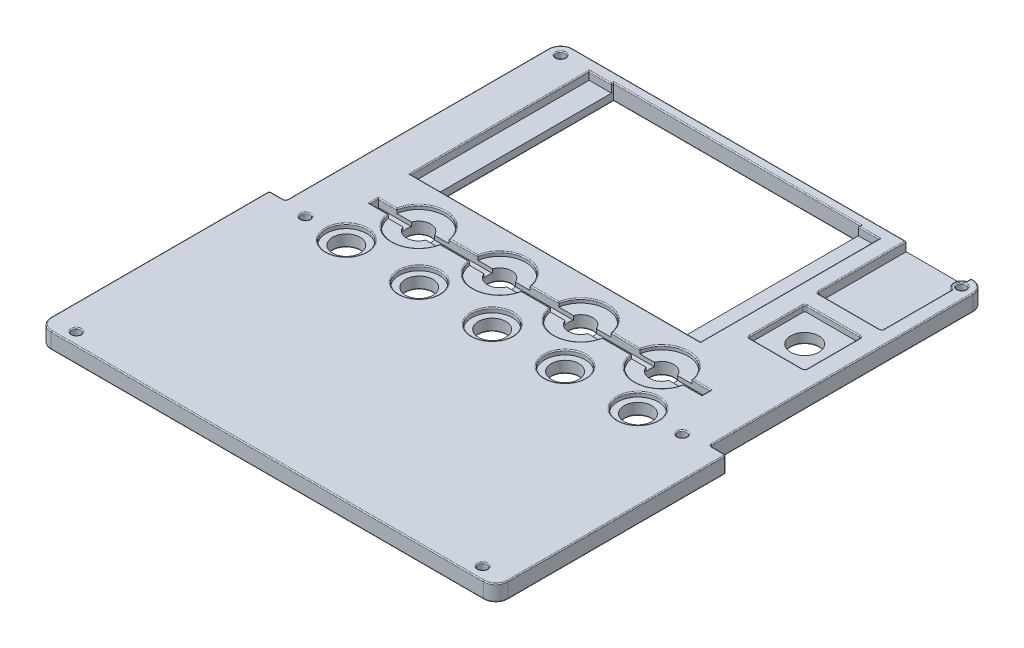
SolidWorks part; units mm, degrees
ref_plane "Front Plane" through (0, 0, 0) normal (0, 0, 1) x (1, 0, 0)
ref_plane "Top Plane" through (0, 0, 0) normal (0, 1, 0) x (1, 0, 0)
ref_plane "Right Plane" through (0, 0, 0) normal (1, 0, 0) x (0, 0, -1)
sketch "Sketch1" plane through (0, 0, 0) normal (0, 1, 0) x (1, 0, 0)
  line L0 (112.8, 56.9) -> (108.8, 56.9)
  line L1 (0, 0) -> (112.8, 0)
  line L2 (0, 0) -> (0, 56.9)
  line L3 (0, 56.9) -> (112.8, 56.9) construction
  line L4 (112.8, 0) -> (112.8, 56.9)
  line L5 (4, 56.9) -> (0, 56.9)
  line L6 (4, 56.9) -> (4, 124.8)
  line L7 (4, 124.8) -> (108.8, 124.8)
  line L8 (108.8, 56.9) -> (108.8, 124.8)
  line L9 (0, 56.9) -> (112.8, 56.9) construction
  dimension "D1" = 104.8
  dimension "D2" = 112.8
  dimension "D3" = 67.9
  dimension "D4" = 56.9
extrude "Main" add sketch "Sketch1" along normal blind 4
sketch "Outline Display" plane through (0, 0, 0) normal (0, -1, 0) x (1, 0, 0)
  line L0 (4, -124.8) -> (4, -81.05) construction
  line L1 (4, -124.8) -> (4, -56.9) construction
  line L2 (4, -81.05) -> (17, -81.05) construction
  line L3 (17, -81.05) -> (17, -78.32) construction
  line L4 (14.23, -78.32) -> (85.03, -78.32) construction
  line L5 (14.23, -78.32) -> (14.23, -121.62) construction
  line L6 (14.23, -121.62) -> (85.03, -121.62) construction
  line L7 (85.03, -78.32) -> (85.03, -121.62) construction
  line L8 (17, -81.05) -> (14.23, -81.05) construction
  point P7 (17, -81.05)
  dimension "D1" = 43.75
  dimension "D2" = 13
  dimension "D3" = 2.73
  dimension "D4" = 2.77
  dimension "D5" = 43.3
  dimension "D6" = 70.8
sketch "Display PCB Notch" plane through (0, 4, 0) normal (0, -1, 0) x (1, 0, 0)
  line L0 (14.23, -78.32) -> (14.23, -77.92) construction
  line L1 (13.83, -77.92) -> (85.43, -77.92)
  line L2 (13.83, -77.92) -> (13.83, -122.02)
  line L3 (13.83, -122.02) -> (85.43, -122.02)
  line L4 (85.43, -77.92) -> (85.43, -122.02)
  line L5 (14.23, -78.32) -> (13.83, -78.32) construction
  line L6 (85.03, -121.62) -> (85.03, -122.02) construction
  line L7 (85.03, -121.62) -> (85.43, -121.62) construction
  dimension "D2" = 0.4
extrude "PCB Notch" cut sketch "Display PCB Notch" along normal blind 2
sketch "Sketch4" plane through (0, 0, 0) normal (0, -1, 0) x (-1, 0, 0)
  line L0 (-14.23, 78.32) -> (-85.03, 78.32) construction
  line L1 (-19.33, 78.87) -> (-80.29, 78.87)
  line L2 (-19.33, 78.87) -> (-19.33, 122.57)
  line L3 (-19.33, 122.57) -> (-80.29, 122.57)
  line L4 (-80.29, 78.87) -> (-80.29, 122.57)
  dimension "D1" = 5.1
  dimension "D2" = 0.55
  dimension "D3" = 60.96
  dimension "D4" = 43.7
extrude "Display Cut" cut sketch "Sketch4" against normal up to next
sketch "Sketch5" plane through (0, 0, 0) normal (0, -1, 0) x (1, 0, 0)
  line L0 (108.8, -56.9) -> (108.8, -124.8) construction
  line L1 (89.12, -102.2) -> (97.32, -102.2) construction
  line L2 (97.32, -102.2) -> (97.32, -91.75) construction
  circle A0 centre (97.32, -91.75) radius 3.5
  point P0 (89.12, -102.2)
  point P1 (108.8, -124.8)
  point P9 (97.32, -91.75)
  dimension "D5" = 7
  dimension "D1" = 22.6
  dimension "D2" = 19.68
  dimension "D3" = 10.45
  dimension "D4" = 8.2
extrude "Rotary Hole" cut sketch "Sketch5" against normal up to next
sketch "Sketch6" plane through (0, 0, 0) normal (0, -1, 0) x (1, 0, 0)
  line L0 (6.9, -124.8) -> (6.9, -121.9) construction
  line L1 (108.8, -124.8) -> (4, -124.8) construction
  line L2 (6.9, -121.9) -> (4, -121.9) construction
  line L3 (4, -124.8) -> (4, -56.9) construction
  line L4 (56.4, 0) -> (56.4, -124.8) construction
  line L5 (0, 0) -> (112.8, 0) construction
  line L6 (0, -55.9) -> (9.9, -55.9) construction
  line L7 (0, -56.9) -> (0, 0) construction
  line L8 (4, -56.9) -> (0, -56.9) construction
  line L9 (0, -3) -> (6.25, -3) construction
  circle A0 centre (6.9, -121.9) radius 1.1
  circle A1 centre (9.9, -55.9) radius 1.1
  circle A2 centre (6.25, -3) radius 1.1
  circle A3 centre (105.9, -121.9) radius 1.1
  circle A4 centre (102.9, -55.9) radius 1.1
  circle A5 centre (106.55, -3) radius 1.1
  dimension "D1" = 2.2
  dimension "D7" = 6.25
  dimension "D2" = 2.9
  dimension "D3" = 2.9
  dimension "D4" = 9.9
  dimension "D5" = 1
  dimension "D6" = 3
extrude "Mounts" cut sketch "Sketch6" against normal up to next contours A0 | A1 | A2 | A5 | A4 | A3
fillet "Fillet1" radius 3 4 edges at (112.8, 2, 0) (108.8, 2, -124.8) (4, 2, -124.8) (0, 2, 0)
sketch "Sketch7" plane through (0, 0, 0) normal (0, -1, 0) x (1, 0, 0)
  line L0 (17, -81.05) -> (17, -75.8) construction
  line L1 (17, -59.7) -> (4, -59.7) construction
  line L2 (17, -75.8) -> (95.8, -75.8)
  line L3 (17, -75.8) -> (17, -59.7)
  line L4 (17, -59.7) -> (95.8, -59.7)
  line L5 (95.8, -75.8) -> (95.8, -59.7)
  line L6 (4, -121.8) -> (4, -56.9) construction
  line L7 (95.8, -59.7) -> (108.8, -59.7) construction
  line L8 (108.8, -56.9) -> (108.8, -121.8) construction
  line L9 (17, -67.75) -> (95.8, -67.75) construction
  circle A0 centre (26, -67.75) radius 3
  circle A1 centre (46, -67.75) radius 3
  circle A2 centre (66, -67.75) radius 3
  circle A3 centre (86, -67.75) radius 3
  dimension "D3" = 6
  dimension "D1" = 5.25
  dimension "D2" = 16.1
  dimension "D4" = 9
  dimension "D5" = 20
  dimension "D6" = 20
  dimension "D7" = 20
extrude "Toggle Mounts" cut sketch "Sketch7" against normal up to next contours A0 | A1 | A2 | A3
sketch "Sketch8" plane through (0, 4, 0) normal (0, -1, 0) x (1, 0, 0)
  line L0 (89, -67.75) -> (23, -67.75) construction
  line L1 (97, -67.75) -> (89, -67.75) construction
  line L2 (97, -68.8) -> (15, -68.8)
  line L3 (97, -68.8) -> (97, -66.7)
  line L4 (97, -66.7) -> (15, -66.7)
  line L5 (15, -68.8) -> (15, -66.7)
  line L6 (23, -67.75) -> (15, -67.75) construction
  line L7 (23, -67.75) -> (23, -68.8) construction
  line L8 (23, -67.75) -> (23, -66.7) construction
  circle A0 centre (86, -67.75) radius 3 construction
  circle A1 centre (26, -67.75) radius 3 construction
  circle A2 centre (86, -67.75) radius 3 construction
  circle A3 centre (86, -67.75) radius 3 construction
  circle A4 centre (26, -67.75) radius 3 construction
  circle A5 centre (26, -67.75) radius 3 construction
  dimension "D1" = 8
  dimension "D2" = 2.1
extrude "Toggle Direction" cut sketch "Sketch8" along normal blind 2
sketch "Sketch9" plane through (0, 4, 0) normal (0, 1, 0) x (1, 0, 0)
  circle A0 centre (26, 67.75) radius 6.5
  circle A1 centre (46, 67.75) radius 6.5
  circle A2 centre (66, 67.75) radius 6.5
  circle A3 centre (86, 67.75) radius 6.5
  point P0 (26, 67.75)
  point P1 (46, 67.75)
  point P3 (66, 67.75)
  point P5 (86, 67.75)
  dimension "D1" = 13
extrude "Toggle Countersinks" cut sketch "Sketch9" against normal blind 1
sketch "Sketch10" plane through (0, 4, 0) normal (0, 1, 0) x (1, 0, 0)
  line L1 (90.32, 98.75) -> (104.32, 98.75)
  line L2 (90.32, 98.75) -> (90.32, 84.75)
  line L3 (90.32, 84.75) -> (104.32, 84.75)
  line L4 (104.32, 98.75) -> (104.32, 84.75)
  line L5 (90.32, 98.75) -> (104.32, 84.75) construction
  line L6 (90.32, 84.75) -> (104.32, 98.75) construction
  point P0 (97.32, 91.75)
  point P1 (97.32, 91.75)
  dimension "D1" = 14
extrude "Encoder Clearance" cut sketch "Sketch10" against normal blind 1.5
sketch "Sketch11" plane through (0, 4, 0) normal (0, 1, 0) x (1, 0, 0)
  line L0 (105.8, 124.8) -> (7, 124.8) construction
  line L1 (89.32, 102.75) -> (105.32, 102.75)
  line L2 (89.32, 102.75) -> (89.32, 124.8)
  line L3 (89.32, 124.8) -> (105.32, 124.8)
  line L4 (105.32, 102.75) -> (105.32, 120.0907)
  line L5 (89.32, 102.75) -> (105.32, 124.8) construction
  line L6 (89.32, 124.8) -> (105.32, 102.75) construction
  line L7 (105.32, 123.7093) -> (105.32, 124.8)
  line L8 (105.32, 120.0907) -> (105.32, 123.7093) construction
  line L10 (104.32, 84.75) -> (104.32, 98.75)
  line L11 (104.32, 98.75) -> (90.32, 98.75)
  line L12 (90.32, 98.75) -> (90.32, 84.75)
  line L13 (90.32, 84.75) -> (104.32, 84.75)
  line L14 (104.32, 84.75) -> (104.32, 98.75) construction
  line L15 (104.32, 98.75) -> (90.32, 98.75) construction
  line L16 (90.32, 98.75) -> (90.32, 84.75) construction
  line L17 (90.32, 84.75) -> (104.32, 84.75) construction
  arc A0 (105.32, 123.7093) -> (105.32, 120.0907) centre (105.9, 121.9) ccw
  circle A1 centre (105.9, 121.9) radius 1.1 construction
  arc A2 (105.32, 120.0907) -> (105.32, 123.7093) centre (105.9, 121.9) ccw construction
  point P4 (97.32, 113.775)
  dimension "D5" = 3.8
  dimension "D2" = 1
  dimension "D3" = 1
  dimension "D4" = 4
  dimension "D1" = 0
extrude "Encoder Pin Clearance" cut sketch "Sketch11" against normal blind 2.3
fillet "Fillet2" radius 0.5 10 edges at (0, 2, -56.9) (4, 2, -56.9) (112.8, 2, -56.9) (108.8, 2, -56.9) (89.32, 2.85, -102.75) (105.32, 2.85, -102.75) (104.32, 3.25, -84.75) (104.32, 3.25, -98.75) (90.32, 3.25, -98.75) (90.32, 3.25, -84.75)
sketch "Sketch12" plane through (0, 4, 0) normal (0, 1, 0) x (1, 0, 0)
  line L0 (9.9, 55.9) -> (102.9, 55.9) construction
  line L1 (38, 66.7) -> (38, 59.3) construction
  line L3 (56, 66.7) -> (56, 59.3) construction
  line L4 (59.5854, 66.7) -> (52.4146, 66.7) construction
  line L5 (74, 66.7) -> (74, 59.3) construction
  line L7 (38, 59.3) -> (20, 59.3) construction
  line L8 (38, 59.3) -> (56, 59.3) construction
  line L9 (74, 59.3) -> (92, 59.3) construction
  line L10 (56, 59.3) -> (74, 59.3) construction
  circle A2 centre (20, 55.9) radius 3.4
  circle A3 centre (38, 55.9) radius 3.4
  circle A4 centre (56, 55.9) radius 3.4
  circle A5 centre (74, 55.9) radius 3.4
  circle A6 centre (92, 55.9) radius 3.4
  point P3 (9.9, 55.9)
  point P4 (102.9, 55.9)
  dimension "D1" = 6.8
  dimension "D2" = 18
extrude "LED Mounts" cut sketch "Sketch12" against normal up to next
sketch "Sketch13" plane through (0, 4, 0) normal (0, 1, 0) x (1, 0, 0)
  circle A0 centre (20, 55.9) radius 5
  circle A1 centre (38, 55.9) radius 5
  circle A2 centre (56, 55.9) radius 5
  circle A3 centre (74, 55.9) radius 5
  circle A4 centre (92, 55.9) radius 5
  point P0 (20, 55.9)
  point P1 (38, 55.9)
  point P3 (56, 55.9)
  point P5 (74, 55.9)
  point P7 (92, 55.9)
  dimension "D1" = 10
extrude "LED Countersink" cut sketch "Sketch13" against normal blind 1.1
fillet "Fillet4" radius 0.25 77 edges at (4.8787, 4, -123.9213) (105.56, 4, -124.8) (48.16, 4, -124.8) (111.9213, 4, -0.8787) (56.4, 4, 0) (56.4, 0, -124.8) (112.8, 0, -29.7) (111.9213, 0, -0.8787) (56.4, 0, 0) (108.9464, 4, -57.0464) (108.9464, 0, -57.0464) (3.8536, 4, -57.0464) (3.8536, 0, -57.0464) (90.4664, 4, -84.8964) (90.4664, 4, -98.6036) (104.1736, 4, -98.6036) (104.1736, 4, -84.8964) (89.4664, 4, -102.8964) (0.1464, 4, -56.7536) (107.9213, 4, -123.9213) (107.9213, 0, -123.9213) (0.8787, 0, -0.8787) (108.8, 4, -89.6) (110.8, 4, -56.9) (112.8, 4, -29.7) (0, 4, -29.7) (2, 0, -56.9) (108.8, 0, -89.6) (49.63, 4, -77.92) (85.43, 4, -99.97) (82.86, 4, -122.02) (16.58, 4, -122.02) (13.83, 4, -99.97) (49.81, 0, -78.87) (80.29, 0, -100.72) (19.33, 0, -100.72) (97.32, 0, -95.25) (9.9, 0, -57) (6.25, 4, -1.9) (106.55, 0, -1.9) (106.55, 4, -1.9) (102.9, 0, -54.8) (102.9, 4, -54.8) (105.9, 0, -120.8) (105.9, 4, -120.8) (26, 0, -70.75) (46, 0, -70.75) (86, 0, -70.75) (17.2927, 4, -68.8) (36, 4, -68.8) (56, 4, -68.8) (94.7073, 4, -68.8) (15, 4, -67.75) (94.7073, 4, -66.7) (56, 4, -66.7) (17.2927, 4, -66.7) (97, 4, -67.75) (46, 4, -74.25) (66, 4, -74.25) (66, 4, -61.25) (86, 4, -74.25) (86, 4, -61.25) (97.32, 4, -84.75) (104.32, 4, -91.75) (97.32, 4, -102.75) (92, 0, -52.5) (20, 0, -52.5) (74, 0, -52.5) (20, 4, -50.9) (38, 4, -50.9) (56, 4, -50.9) (92, 4, -50.9) (6.9, 4, -120.8) (80.29, 4, -122.295) (19.33, 4, -122.295) (6.9, 0, -123) (104, 4, -121.9)
